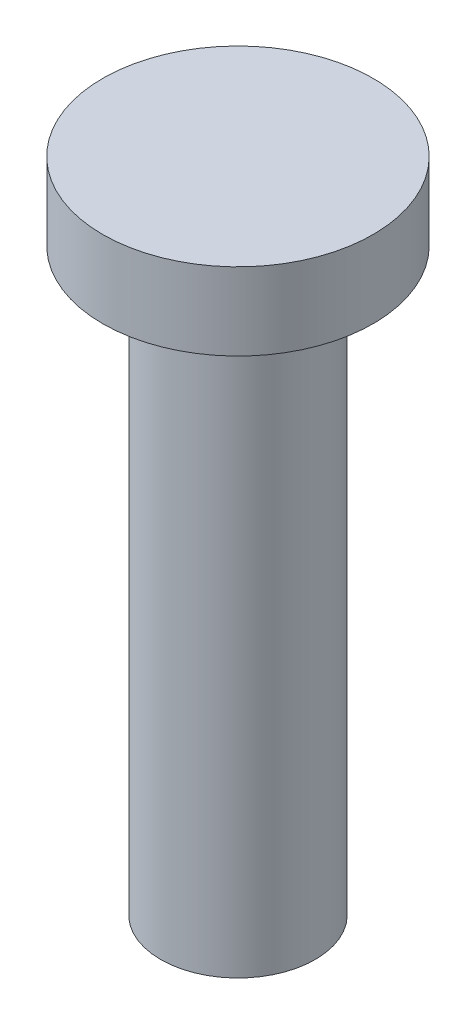
SolidWorks part; units mm, degrees
ref_plane "Plan de face" through (0, 0, 0) normal (0, 0, 1) x (1, 0, 0)
ref_plane "Plan de dessus" through (0, 0, 0) normal (0, 1, 0) x (1, 0, 0)
ref_plane "Plan de droite" through (0, 0, 0) normal (1, 0, 0) x (0, 0, -1)
sketch "Esquisse1" plane through (0, 0, 0) normal (0, 1, 0) x (1, 0, 0)
  circle A0 centre (0, 0) radius 2
  dimension "D1" = 4
extrude "Extrusion1" add sketch "Esquisse1" along normal blind 15
sketch "Esquisse2" plane through (0, 15, 0) normal (0, 1, 0) x (1, 0, 0)
  circle A0 centre (0, 0) radius 3.5
  dimension "D1" = 7
extrude "Extrusion2" add sketch "Esquisse2" along normal blind 2
